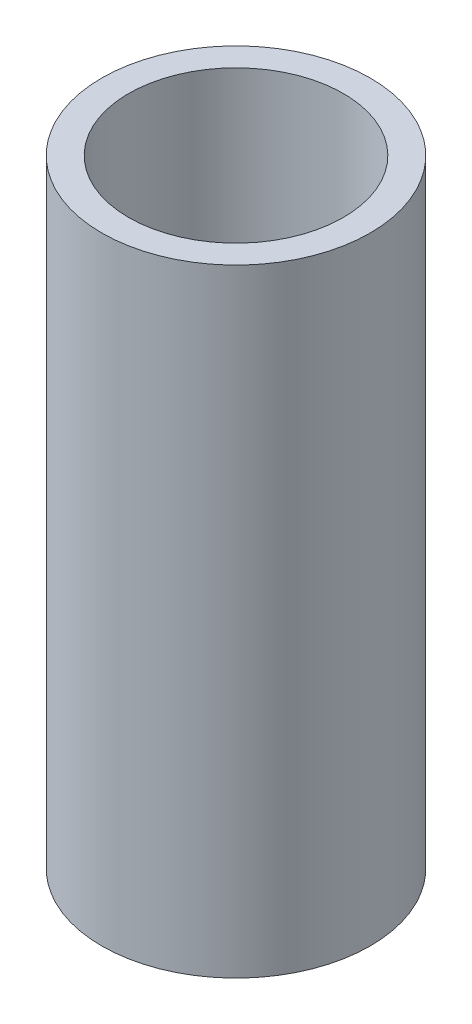
SolidWorks part; units mm, degrees
ref_plane "Front Plane" through (0, 0, 0) normal (0, 0, 1) x (1, 0, 0)
ref_plane "Top Plane" through (0, 0, 0) normal (0, 1, 0) x (1, 0, 0)
ref_plane "Right Plane" through (0, 0, 0) normal (1, 0, 0) x (0, 0, -1)
sketch "Sketch1" plane through (0, 0, 0) normal (0, 1, 0) x (1, 0, 0)
  circle A0 centre (0, 0) radius 4
  circle A1 centre (0, 0) radius 5
  dimension "D1" = 8
  dimension "D2" = 10
extrude "Boss-Extrude1" add sketch "Sketch1" along normal blind 23
